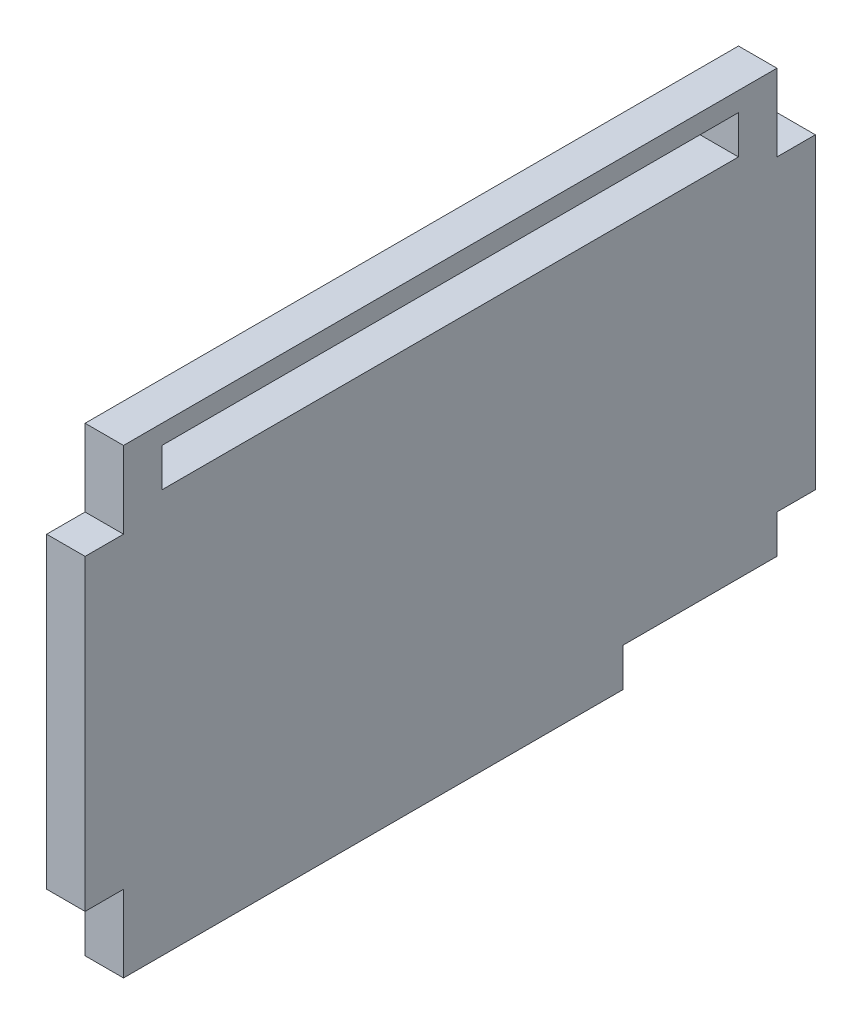
SolidWorks part; units mm, degrees
ref_plane "Front Plane" through (0, 0, 0) normal (0, 0, 1) x (1, 0, 0)
ref_plane "Top Plane" through (0, 0, 0) normal (0, 1, 0) x (1, 0, 0)
ref_plane "Right Plane" through (0, 0, 0) normal (1, 0, 0) x (0, 0, -1)
sketch "Sketch1" plane through (0, 0, 0) normal (0, 0, 1) x (1, 0, 0)
  line L0 (-44.45, 38.1) -> (38.1, 38.1) construction
  line L1 (-44.45, -38.1) -> (-38.1, -38.1)
  line L2 (-44.45, -38.1) -> (-44.45, 38.1)
  line L3 (-44.45, 38.1) -> (-38.1, 38.1)
  line L4 (-38.1, -38.1) -> (-38.1, 38.1)
  dimension "D1" = 6.35
extrude "Boss-Extrude1" add sketch "Sketch1" along normal blind 114.3
sketch "Sketch2" plane through (-38.1, 0, 0) normal (1, 0, 0) x (0, 0, -1)
  line L0 (0, -38.1) -> (0, 38.1) construction
  line L1 (0, 25.4) -> (6.35, 25.4)
  line L2 (0, 25.4) -> (0, -25.4)
  line L3 (0, -25.4) -> (6.35, -25.4)
  line L4 (6.35, 25.4) -> (6.35, -25.4)
  line L5 (-114.3, -38.1) -> (0, -38.1) construction
  line L6 (-114.3, 38.1) -> (0, 38.1) construction
  dimension "D1" = 6.35
  dimension "D2" = 12.7
  dimension "D3" = 12.7
extrude "Boss-Extrude2" add sketch "Sketch2" against normal through all
sketch "Sketch3" plane through (-38.1, 0, 0) normal (1, 0, 0) x (0, 0, -1)
  line L1 (-107.95, -25.4) -> (-114.3, -25.4)
  line L2 (-107.95, -25.4) -> (-107.95, -38.1)
  line L3 (-107.95, -38.1) -> (-114.3, -38.1)
  line L4 (-114.3, -25.4) -> (-114.3, -38.1)
  line L5 (-107.95, 25.4) -> (-114.3, 25.4)
  line L6 (-107.95, 25.4) -> (-107.95, 38.1)
  line L7 (-107.95, 38.1) -> (-114.3, 38.1)
  line L8 (-114.3, 25.4) -> (-114.3, 38.1)
  line L9 (-101.6, 28.575) -> (-6.35, 28.575)
  line L10 (-101.6, 28.575) -> (-101.6, 34.925)
  line L11 (-101.6, 34.925) -> (-6.35, 34.925)
  line L12 (-6.35, 28.575) -> (-6.35, 34.925)
  line L13 (0, -38.1) -> (-25.4, -38.1)
  line L14 (0, -38.1) -> (0, -31.75)
  line L15 (0, -31.75) -> (-25.4, -31.75)
  line L16 (-25.4, -38.1) -> (-25.4, -31.75)
extrude "Cut-Extrude1" cut sketch "Sketch3" against normal through all
